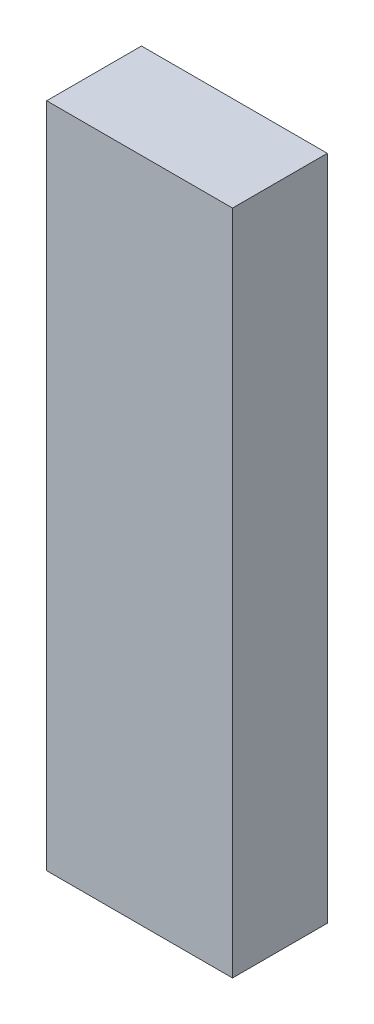
SolidWorks part; units mm, degrees
ref_plane "Přední rovina" through (0, 0, 0) normal (0, 0, 1) x (1, 0, 0)
ref_plane "Horní rovina" through (0, 0, 0) normal (0, 1, 0) x (1, 0, 0)
ref_plane "Pravá rovina" through (0, 0, 0) normal (1, 0, 0) x (0, 0, -1)
sketch "Skica1" plane through (0, 0, 0) normal (0, 0, 1) x (1, 0, 0)
  line L1 (-2.45, 8.79) -> (2.45, 8.79)
  line L2 (-2.45, 8.79) -> (-2.45, -8.79)
  line L3 (-2.45, -8.79) -> (2.45, -8.79)
  line L4 (2.45, 8.79) -> (2.45, -8.79)
  line L5 (-2.45, 8.79) -> (2.45, -8.79) construction
  line L6 (-2.45, -8.79) -> (2.45, 8.79) construction
  point P0 (0, 0)
  dimension "D1" = 17.58
  dimension "D2" = 4.9
extrude "Přidat vysunutím1" add sketch "Skica1" along normal blind 2.5
